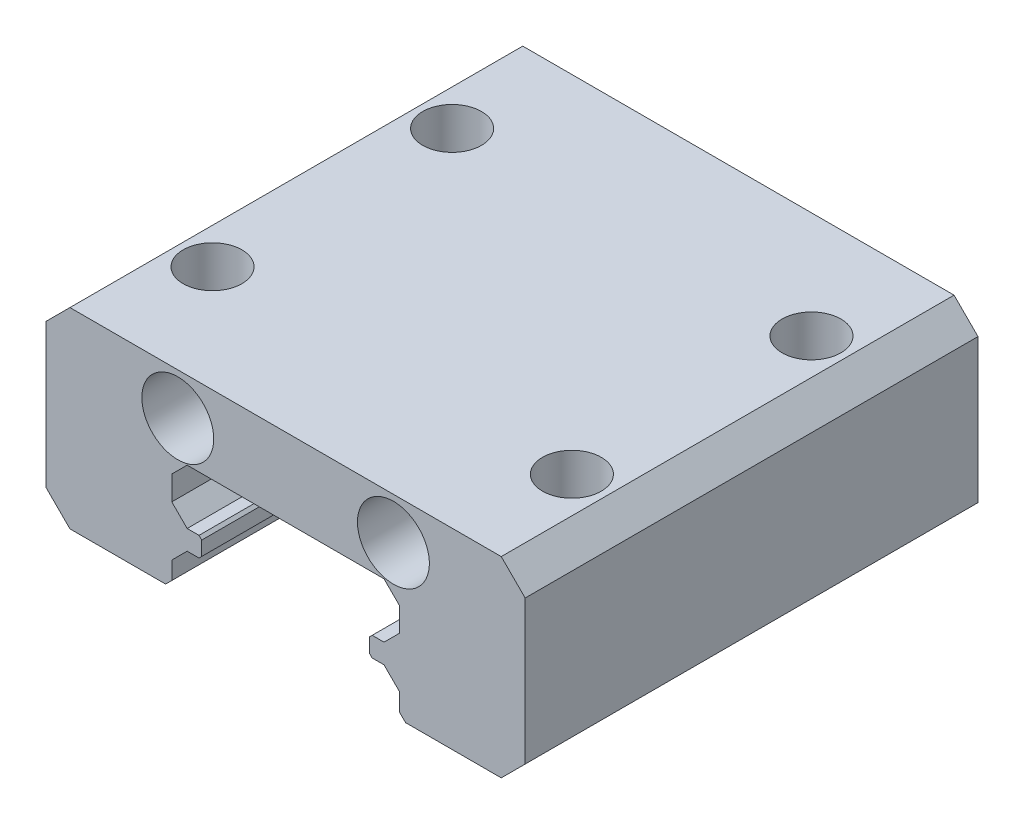
SolidWorks part; units mm, degrees
ref_plane "前视基准面" through (0, 0, 0) normal (0, 0, 1) x (1, 0, 0)
ref_plane "上视基准面" through (0, 0, 0) normal (0, 1, 0) x (1, 0, 0)
ref_plane "右视基准面" through (0, 0, 0) normal (1, 0, 0) x (0, 0, -1)
sketch "Sketch2" plane through (0, 0, 0) normal (0, 0, 1) x (1, 0, 0)
  line L0 (-4.005, 6.5) -> (4.005, 6.5) construction
  line L1 (4.005, 6.5) -> (4.5, 6.005) construction
  line L2 (4.5, 6.005) -> (4.5, 5.205) construction
  line L3 (4.5, 5.205) -> (4.005, 4.7101) construction
  line L4 (4.005, 4.7101) -> (3.5101, 4.7101) construction
  line L5 (3.5101, 4.7101) -> (3.25, 4.45) construction
  line L6 (3.25, 4.45) -> (3.25, 3.65) construction
  line L7 (3.25, 3.65) -> (3.5101, 3.3899) construction
  line L8 (3.5101, 3.3899) -> (4.005, 3.3899) construction
  line L9 (4.005, 3.3899) -> (4.5, 2.895) construction
  line L10 (4.5, 2.895) -> (4.5, 0.495) construction
  line L11 (4.5, 0.495) -> (4.005, 0) construction
  line L12 (4.005, 0) -> (-4.005, 0) construction
  line L13 (0, 0) -> (0, 6.5) construction
  line L14 (-4.5, 0.495) -> (-4.005, 0) construction
  line L15 (-4.5, 2.895) -> (-4.5, 0.495) construction
  line L16 (-4.005, 3.3899) -> (-4.5, 2.895) construction
  line L17 (-3.5101, 3.3899) -> (-4.005, 3.3899) construction
  line L18 (-3.25, 3.65) -> (-3.5101, 3.3899) construction
  line L19 (-3.25, 4.45) -> (-3.25, 3.65) construction
  line L20 (-3.5101, 4.7101) -> (-3.25, 4.45) construction
  line L21 (-4.005, 4.7101) -> (-3.5101, 4.7101) construction
  line L22 (-4.5, 5.205) -> (-4.005, 4.7101) construction
  line L23 (-4.5, 6.005) -> (-4.5, 5.205) construction
  line L24 (-4.005, 6.5) -> (-4.5, 6.005) construction
  line L25 (-4.1086, 6.75) -> (4.1086, 6.75)
  line L26 (4.1086, 6.75) -> (4.75, 6.1086)
  line L27 (4.75, 6.1086) -> (4.75, 5.1015)
  line L28 (4.75, 5.1015) -> (4.1086, 4.4601)
  line L29 (4.1086, 4.4601) -> (3.6136, 4.4601)
  line L30 (3.6136, 4.4601) -> (3.5, 4.3464)
  line L31 (3.5, 4.3464) -> (3.5, 3.7536)
  line L32 (3.5, 3.7536) -> (3.6136, 3.6399)
  line L33 (3.6136, 3.6399) -> (4.1086, 3.6399)
  line L34 (4.1086, 3.6399) -> (4.75, 2.9985)
  line L35 (4.75, 2.9985) -> (4.75, 2.2579)
  line L40 (-4.1086, 3.6399) -> (-4.75, 2.9985)
  line L41 (-3.6136, 3.6399) -> (-4.1086, 3.6399)
  line L42 (-3.5, 3.7536) -> (-3.6136, 3.6399)
  line L43 (-3.5, 4.3464) -> (-3.5, 3.7536)
  line L44 (-3.6136, 4.4601) -> (-3.5, 4.3464)
  line L45 (-4.1086, 4.4601) -> (-3.6136, 4.4601)
  line L46 (-4.75, 5.1015) -> (-4.1086, 4.4601)
  line L47 (-4.75, 6.1086) -> (-4.75, 5.1015)
  line L48 (-4.1086, 6.75) -> (-4.75, 6.1086)
  line L49 (9.0015, 10) -> (-9.0015, 10)
  line L51 (4.1086, -0.25) -> (-4.1086, -0.25) construction
  line L52 (-4.75, 0.3914) -> (-4.1086, -0.25) construction
  line L53 (4.75, 0.3914) -> (4.1086, -0.25) construction
  line L54 (-10, 9.0015) -> (-10, 2.9985)
  line L56 (-9.0015, 2) -> (-5.0079, 2)
  line L57 (-5.0079, 2) -> (-4.75, 2.2579)
  line L58 (0, 10) -> (0, 6.75) construction
  line L59 (-4.75, 2.2579) -> (-4.75, 2.9985)
  line L60 (-4.75, 2.9985) -> (-4.75, 0.3914) construction
  line L61 (5.0079, 2) -> (4.75, 2.2579)
  line L62 (9.0015, 2) -> (5.0079, 2)
  line L63 (10, 2.9985) -> (9.0015, 2)
  line L64 (10, 9.0015) -> (10, 2.9985)
  line L65 (9.0015, 10) -> (10, 9.0015)
  line L66 (-9.0015, 10) -> (-10, 9.0015)
  line L67 (4.75, 2.9985) -> (4.75, 0.3914) construction
  line L68 (-10, 2.9985) -> (-9.0015, 2)
  point P11 (-10, 2.9985)
  point P38 (-4.75, 2.2579)
  point P39 (-9.0015, 10)
  dimension "D1" = 6.5
  dimension "D2" = 4.5
  dimension "D3" = 0.8
  dimension "D4" = 135
  dimension "D5" = 0.7
  dimension "D6" = 6.5
  dimension "D7" = 2.4
  dimension "D8" = 0.8
  dimension "D10" = 10
  dimension "D11" = 8
  dimension "D12" = 10
  dimension "D13" = 135
  dimension "D14" = 135
  dimension "D9" = 0.25
extrude "Boss-Extrude1" add sketch "Sketch2" along normal mid plane 18.9
sketch "Sketch3" plane through (0, 0, 9.45) normal (0, 0, 1) x (1, 0, 0)
  line L0 (-4.1086, 6.75) -> (4.1086, 6.75) construction
  line L1 (0, 6.75) -> (0, 10) construction
  line L2 (9.0015, 10) -> (-9.0015, 10) construction
  circle A0 centre (-4.5, 8.25) radius 1.5
  circle A1 centre (4.5, 8.25) radius 1.5
  dimension "D1" = 3
  dimension "D2" = 4.5
  dimension "D3" = 1.5
extrude "Cut-Extrude1" cut sketch "Sketch3" against normal blind 3
mirror "Mirror1" about plane through (0, 0, 0) normal (0, 0, 1) of "Cut-Extrude1"
sketch "Sketch4" plane through (0, 10, 0) normal (0, 1, 0) x (1, 0, 0)
  line L0 (0, -3.021) -> (0, 0) construction
  line L1 (0, 0) -> (-2.215, 0) construction
  circle A0 centre (7.5, -5) radius 1.2263
  circle A1 centre (-7.5, -5) radius 1.2263
  circle A2 centre (-7.5, 5) radius 1.2263
  circle A3 centre (7.5, 5) radius 1.2263
  dimension "D1" = 7.5
  dimension "D2" = 5
  dimension "3" = 2.4525
extrude "Cut-Extrude2" cut sketch "Sketch4" against normal blind 3
